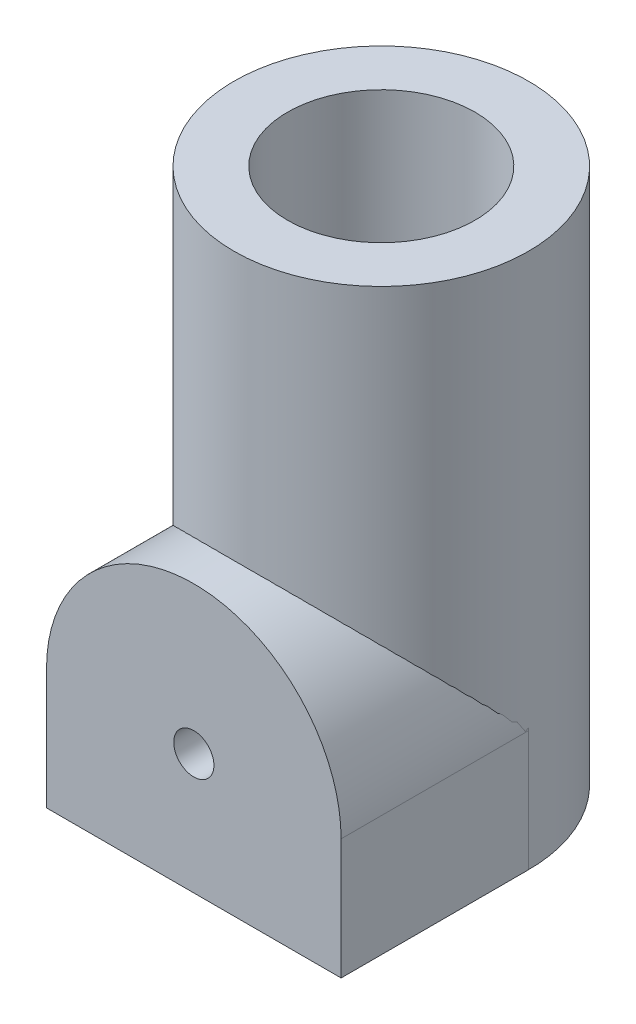
SolidWorks part; units mm, degrees
ref_plane "Front Plane" through (0, 0, 0) normal (0, 0, 1) x (1, 0, 0)
ref_plane "Top Plane" through (0, 0, 0) normal (0, 1, 0) x (1, 0, 0)
ref_plane "Right Plane" through (0, 0, 0) normal (1, 0, 0) x (0, 0, -1)
sketch "Sketch1" plane through (0, 0, 0) normal (0, 1, 0) x (1, 0, 0)
  circle A0 centre (0, 0) radius 5.5
  circle A1 centre (0, 0) radius 3.5
  dimension "D1" = 11
  dimension "D2" = 7
extrude "Boss-Extrude1" add sketch "Sketch1" along normal blind 20
sketch "Sketch2" plane through (0, 0, 0) normal (0, 0, 1) x (1, 0, 0)
  line L1 (-5.5, -10) -> (5.5, -10)
  line L2 (-5.5, -10) -> (-5.5, 10)
  line L3 (-5.5, 10) -> (5.5, 10)
  line L4 (5.5, -10) -> (5.5, 10)
  line L5 (-5.5, -10) -> (5.5, 10) construction
  line L6 (-5.5, 10) -> (5.5, -10) construction
  line L7 (-5.5, 0) -> (5.5, 0)
  line L8 (-5.5, 0) -> (-5.5, 10)
  line L9 (-5.5, 10) -> (5.5, 10)
  line L10 (5.5, 0) -> (5.5, 10)
  circle A0 centre (0, 4.5) radius 5.5
  point P0 (0, 0)
  dimension "D3" = 11
  dimension "D1" = 20
  dimension "D2" = 11
  dimension "D4" = 5.5
extrude "Boss-Extrude2" add sketch "Sketch2" along normal blind 7 separate body contours A0 L7 | A0 L2 L7 | A0 L7 L4
sketch "Sketch3" plane through (0, 0, 7) normal (0, 0, 1) x (1, 0, 0)
  circle A0 centre (0, 4.5) radius 0.75
  dimension "D1" = 1.5
extrude "Cut-Extrude1" cut sketch "Sketch3" against normal blind 30
sketch "Sketch4" plane through (0, 0, 0) normal (1, 0, 0) x (0, 0, -1)
  line L1 (5.4922, 0) -> (-7, 0)
